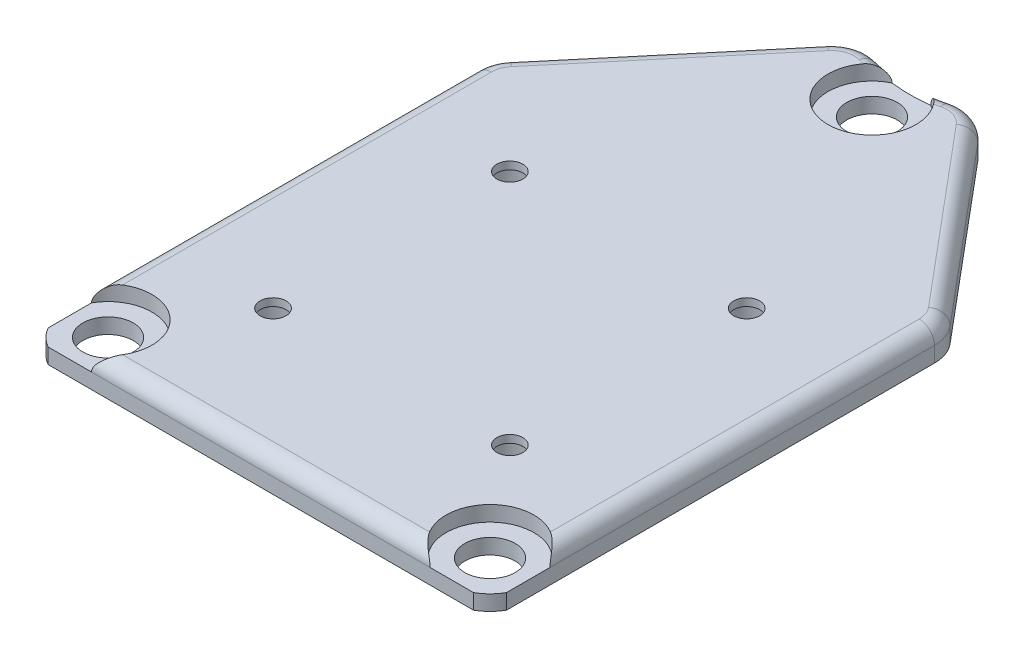
SolidWorks part; units mm, degrees
ref_plane "Front Plane" through (0, 0, 0) normal (0, 0, 1) x (1, 0, 0)
ref_plane "Top Plane" through (0, 0, 0) normal (0, 1, 0) x (1, 0, 0)
ref_plane "Right Plane" through (0, 0, 0) normal (1, 0, 0) x (0, 0, -1)
sketch "Sketch1" plane through (0, 0, 0) normal (0, 1, 0) x (1, 0, 0)
  line L0 (0, 0) -> (0, -72.4) construction
  circle A0 centre (0, -72.4) radius 6.3405 construction
  point P4 (25, -100)
  point P7 (-25, -100)
  point P17 (0, -25)
  dimension "D1" = 72.4
  dimension "D2" = 25
  dimension "D3" = 100
  dimension "D5" = 25
sketch "Sketch2" plane through (0, 0, 0) normal (0, 1, 0) x (1, 0, 0)
  line L0 (-30, -45) -> (-7.7214, -18.4494)
  line L6 (0, 0) -> (0, -72.4) construction
  line L7 (0, -75) -> (0, -52.0117) construction
  line L9 (-30, -105) -> (30, -105)
  line L10 (-30, -105) -> (-30, -45)
  line L12 (30, -105) -> (30, -45)
  line L13 (-30, -105) -> (30, -45) construction
  line L14 (-30, -45) -> (30, -105) construction
  line L15 (7.7214, -18.4494) -> (30, -45)
  arc A0 (-7.7214, -18.4494) -> (7.7214, -18.4494) centre (0, 0) ccw
  point P2 (0, 0)
  point P14 (0, -75)
  point P15 (0, -75)
  dimension "D5" = 220
  dimension "D6" = 220
  dimension "D2" = 20
  dimension "D1" = 25
  dimension "D3" = 60
  dimension "D4" = 60
extrude "Boss-Extrude1" add sketch "Sketch2" along normal blind 4 contours L10 L0 A0 L15 L12 L9
hole_wizard "Hole1" positions "Sketch3" profile "Sketch4" legacy end condition up to next
sketch "Sketch3" plane through (0, 4, 0) normal (0, 1, 0) x (1, 0, 0)
  point P4 (-25, -100)
  point P6 (25, -100)
  point P14 (0, -25)
sketch "Sketch4" plane through (-25, 4, 100) normal (1, 0, 0) x (0, 0, 1)
  line L0 (0, 0) -> (0, 4)
  line L1 (0, 4) -> (3.3, 4)
  line L3 (3.3, 4) -> (3.3, 2)
  line L4 (3.3, 2) -> (5.75, 2)
  line L5 (5.75, 2) -> (5.75, 0)
  line L7 (5.75, 0) -> (0, 0)
  line L11 (0, -6.35) -> (0, 107.95) construction
  dimension "Thru Hole Dia." = 6.6
  dimension "Thru Hole Depth" = 4
  dimension "C'Bore Dia." = 11.5
  dimension "C'Bore Depth" = 2
sketch "Sketch5" plane through (0, 4, 0) normal (0, 1, 0) x (1, 0, 0)
  line L0 (-30, -105) -> (-27.8395, -105) construction
  line L5 (-30, -102.8395) -> (-30, -105)
  line L6 (-30, -105) -> (-27.8395, -105)
  line L11 (0, -105) -> (0, -90.3325) construction
  line L12 (-22.1605, -105) -> (22.1605, -105) construction
  line L13 (30, -105) -> (27.8395, -105)
  line L14 (30, -102.8395) -> (30, -105)
  arc A0 (-30, -102.8395) -> (-27.8395, -105) centre (-25, -100) ccw
  arc A1 (30, -102.8395) -> (27.8395, -105) centre (25, -100) cw
extrude "Cut-Extrude3" cut sketch "Sketch5" against normal through all
sketch "Sketch6" plane through (0, 0, 0) normal (0, -1, 0) x (1, 0, 0)
  line L0 (0, 0) -> (0, 72.4) construction
  point P0 (-15.5, 56.9)
  point P5 (0, 72.4)
  point P8 (-15.5, 87.9)
  point P9 (15.5, 87.9)
  point P10 (15.5, 56.9)
  point P11 (0, 72.4)
  dimension "D1" = 15.5
  dimension "D2" = 15.5
  dimension "D3" = 4
hole_wizard "CBORE for M3 SHCS1" positions "Sketch7" profile "Sketch8" counterbore size "M3" standard "ANSI Metric" end condition through all
sketch "Sketch7" plane through (0, 0, 0) normal (0, -1, 0) x (-1, 0, 0)
  point P0 (-15.5, -56.9)
  point P3 (15.5, -56.9)
  point P6 (15.5, -87.9)
  point P9 (-15.5, -87.9)
sketch "Sketch8" plane through (15.5, 0, 56.9) normal (1, 0, 0) x (0, 0, -1)
  line L0 (0, 0) -> (0, 4)
  line L1 (0, 4) -> (1.7, 4)
  line L3 (1.7, 4) -> (1.7, 3)
  line L4 (1.7, 3) -> (3.25, 3)
  line L5 (3.25, 3) -> (3.25, 0)
  line L7 (3.25, 0) -> (0, 0)
  line L11 (0, -6.35) -> (0, 107.95) construction
  dimension "Thru Hole Dia." = 3.4
  dimension "Thru Hole Depth" = 4
  dimension "C'Bore Dia." = 6.5
  dimension "C'Bore Depth" = 3
fillet "Fillet4" radius 5 4 edges at (-30, 2, 45) (-7.7214, 2, 18.4494) (7.7214, 2, 18.4494) (30, 2, 45)
fillet "Fillet3" radius 2 11 edges at (30, 4, 71.9902) (0, 4, 105) (-30, 4, 71.9902) (-19.3624, 4, 32.3226) (-29.6985, 4, 45.1098) (-3.6995, 4, 19.6549) (-7.6079, 4, 19.4975) (29.6985, 4, 45.1098) (19.3624, 4, 32.3226) (7.6079, 4, 19.4975) (3.6995, 4, 19.6549)
